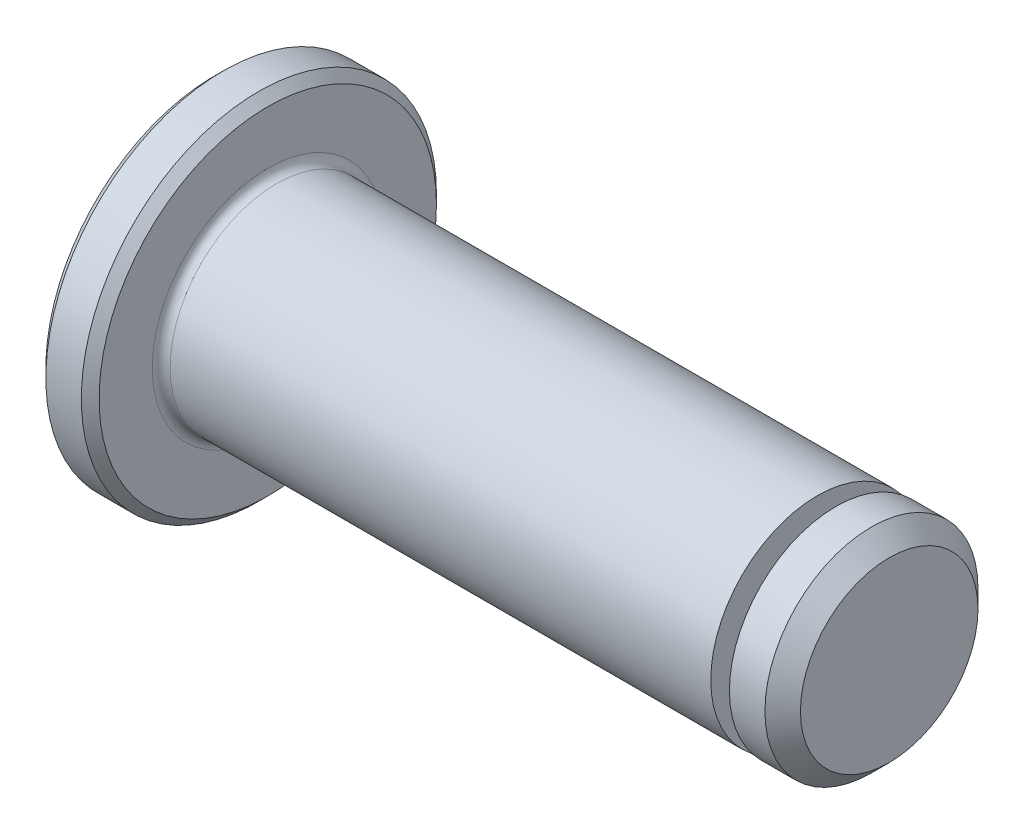
SolidWorks part; units mm, degrees
ref_plane "Piano frontale" through (0, 0, 0) normal (0, 0, 1) x (1, 0, 0)
ref_plane "Piano superiore" through (0, 0, 0) normal (0, 1, 0) x (1, 0, 0)
ref_plane "Piano destro" through (0, 0, 0) normal (1, 0, 0) x (0, 0, -1)
sketch "Schizzo1" plane through (0, 0, 0) normal (1, 0, 0) x (0, 0, -1)
  circle A0 centre (0, 0) radius 10
  dimension "D1" = 20
extrude "Estrusione-Estrusione1" add sketch "Schizzo1" along normal blind 3
sketch "Schizzo2" plane through (3, 0, 0) normal (1, 0, 0) x (0, 0, -1)
  circle A0 centre (0, 0) radius 6
  dimension "D1" = 12
extrude "Estrusione-Estrusione2" add sketch "Schizzo2" along normal blind 35
sketch "Schizzo3" plane through (0, 0, 0) normal (0, 0, 1) x (1, 0, 0)
  line L0 (0, 0) -> (38, 0) construction
  line L1 (38, -6) -> (38, 6) construction
  line L2 (38, 6) -> (3, 6) construction
  line L3 (35, 6) -> (33.95, 6)
  line L4 (35, 6) -> (35, 4)
  line L5 (35, 4) -> (33.95, 4)
  line L6 (33.95, 6) -> (33.95, 4)
  line L7 (3, -6) -> (3, 6) construction
  dimension "D1" = 1.05
  dimension "D2" = 8
  dimension "D3" = 32
revolve "Taglia-Rivoluzione1" cut sketch "Schizzo3" angle 360 about L0
chamfer "Smusso1" distance 1 angle 45 1 edges at (38, 0, -6)
chamfer "Smusso2" distance 0.5 angle 45 2 edges at (0, 0, -10) (3, 0, -10)
fillet "Raccordo1" radius 0.5 1 edges at (3, 0, -6)
